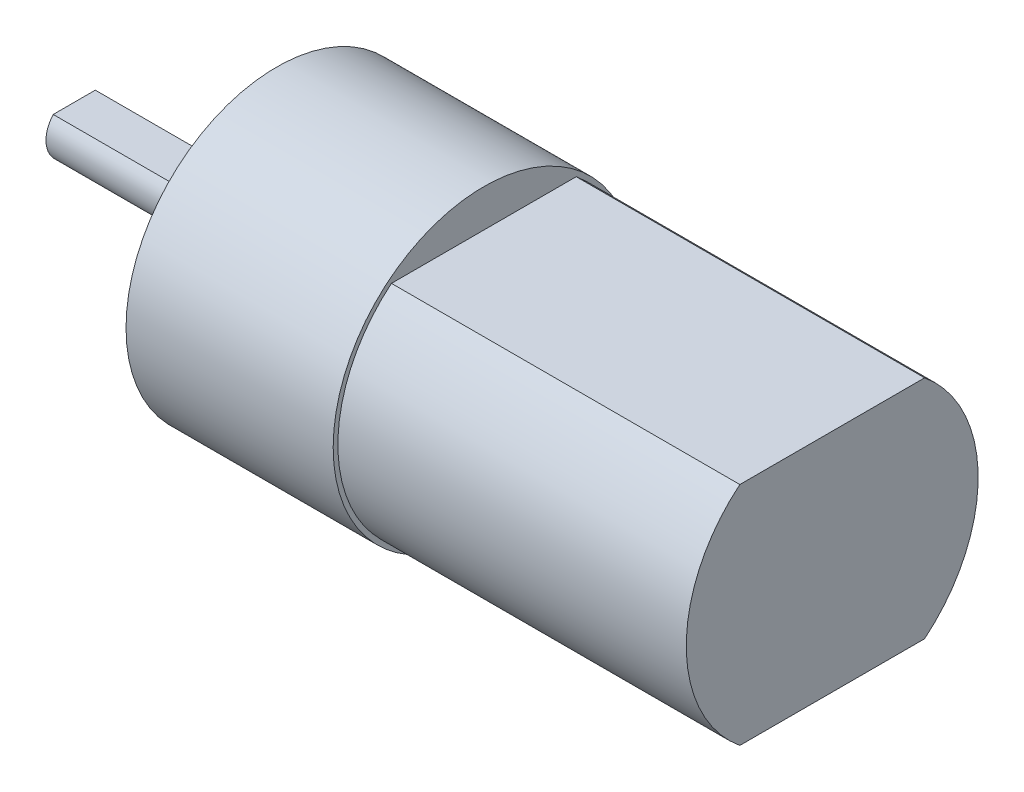
SolidWorks part; units mm, degrees
ref_plane "Front Plane" through (0, 0, 0) normal (0, 0, 1) x (1, 0, 0)
ref_plane "Top Plane" through (0, 0, 0) normal (0, 1, 0) x (1, 0, 0)
ref_plane "Right Plane" through (0, 0, 0) normal (1, 0, 0) x (0, 0, -1)
sketch "Sketch2" plane through (0, 0, 0) normal (1, 0, 0) x (0, 0, -1)
  line L0 (-4.9054, 6) -> (4.9054, 6)
  line L1 (-4.9054, -6) -> (4.9054, -6)
  line L2 (0, 6) -> (0, -6)
  circle A0 centre (0, 0) radius 7.75
  point P9 (0, 0)
  dimension "D1" = 15.5
  dimension "D2" = 12
extrude "Boss-Extrude1" add sketch "Sketch2" along normal blind 18.5 contours L0 A0 L1 L2 | L1 A0 L0 L2
sketch "Sketch3" plane through (0, 0, 0) normal (-1, 0, 0) x (0, 0, 1)
  circle A0 centre (0, 0) radius 8
  dimension "D1" = 16
extrude "Boss-Extrude2" add sketch "Sketch3" along normal blind 11
sketch "Sketch4" plane through (-11, 0, 0) normal (-1, 0, 0) x (0, 0, 1)
  circle A0 centre (0, 0) radius 2
  dimension "D1" = 4
extrude "Boss-Extrude3" add sketch "Sketch4" along normal blind 0.75
sketch "Sketch6" plane through (-11.75, 0, 0) normal (-1, 0, 0) x (0, 0, 1)
  circle A0 centre (0, 0) radius 1.5
  dimension "D1" = 3
extrude "Boss-Extrude4" add sketch "Sketch6" along normal blind 10
sketch "Sketch7" plane through (-21.75, 0, 0) normal (-1, 0, 0) x (0, 0, 1)
  line L0 (-1.118, 1) -> (1.118, 1)
  circle A0 centre (0, 0) radius 1.5 construction
  circle A1 centre (0, 0) radius 1.5
  circle M1 centre (0, 0) radius 1.5
  dimension "D1" = 1
extrude "Cut-Extrude1" cut sketch "Sketch7" along direction (-1, 0, 0) on the side against the normal up to surface (10 mm away) contours L0 M1
sketch "Sketch8" plane through (-11, 0, 0) normal (-1, 0, 0) x (0, 0, 1)
  line L0 (-8, 0) -> (8, 0)
  circle A0 centre (-4.5, 0) radius 1
  circle A1 centre (4.5, 0) radius 1
  circle A2 centre (0, 0) radius 4.5
  circle A3 centre (0, 0) radius 8 construction
  dimension "D1" = 9
  dimension "D2" = 2
extrude "Cut-Extrude2" cut sketch "Sketch8" against normal blind 3 contours A2 A0 L0 | A0 A2 L0 | L0 A2 A0 | A2 L0 A0 | L0 A2 A1 | A2 L0 A1 | A2 A1 L0 | A1 A2 L0
